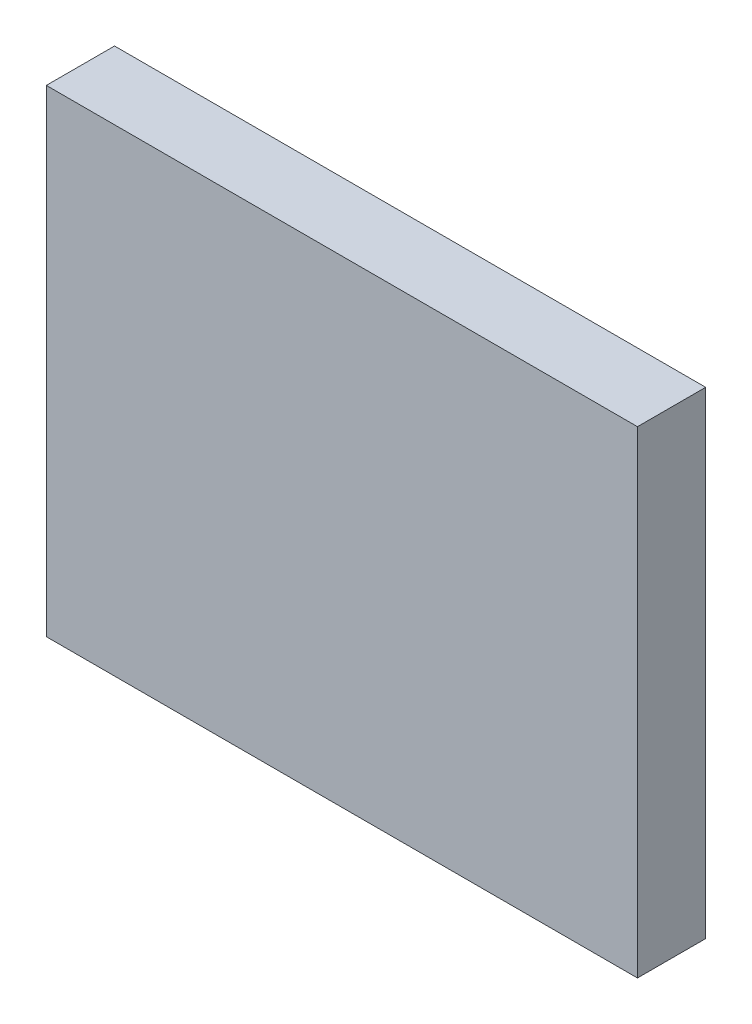
SolidWorks part; units mm, degrees
ref_plane "Спереди" through (0, 0, 0) normal (0, 0, 1) x (1, 0, 0)
ref_plane "Сверху" through (0, 0, 0) normal (0, 1, 0) x (1, 0, 0)
ref_plane "Справа" through (0, 0, 0) normal (1, 0, 0) x (0, 0, -1)
sketch "Эскиз1" plane through (0, 0, 0) normal (0, 0, 1) x (1, 0, 0)
  line L1 (-13, -10.5) -> (13, -10.5)
  line L2 (-13, -10.5) -> (-13, 10.5)
  line L3 (-13, 10.5) -> (13, 10.5)
  line L4 (13, -10.5) -> (13, 10.5)
  line L5 (-13, -10.5) -> (13, 10.5) construction
  line L6 (-13, 10.5) -> (13, -10.5) construction
  point P1 (0, 0)
  dimension "D1" = 21
  dimension "D2" = 26
extrude "Бобышка-Вытянуть1" add sketch "Эскиз1" along normal blind 3
